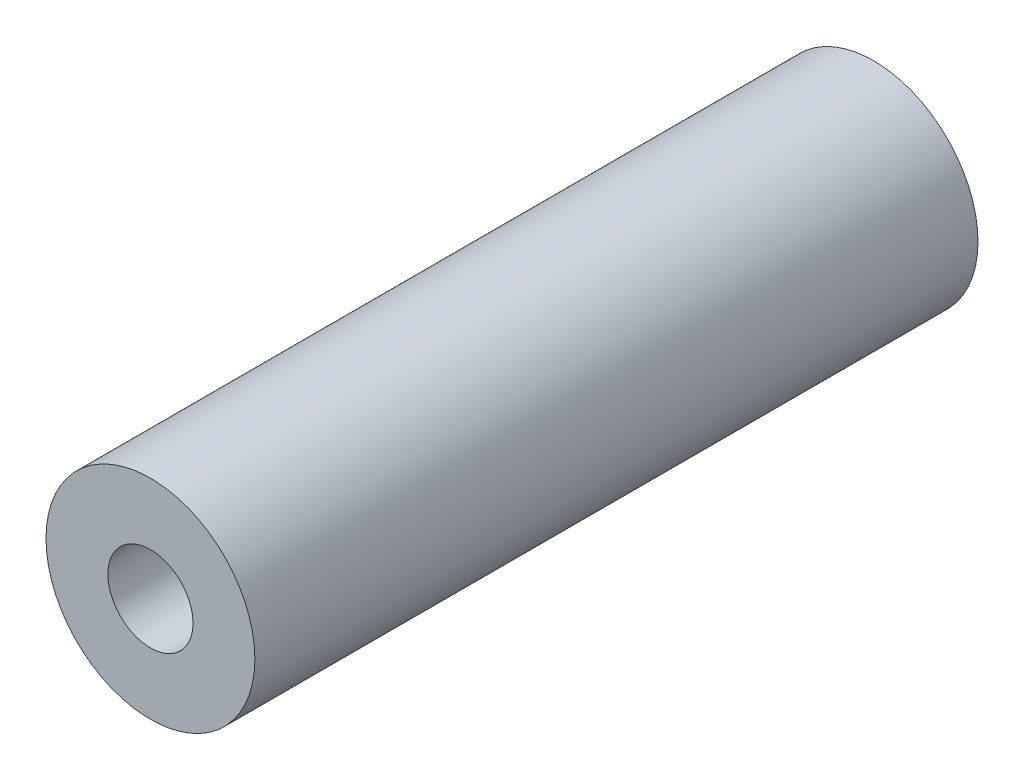
SolidWorks part; units mm, degrees
material "6061-T6 (SS)"
ref_plane "Front Plane" through (0, 0, 0) normal (0, 0, 1) x (1, 0, 0)
ref_plane "Top Plane" through (0, 0, 0) normal (0, 1, 0) x (1, 0, 0)
ref_plane "Right Plane" through (0, 0, 0) normal (1, 0, 0) x (0, 0, -1)
sketch "Sketch1" plane through (0, 0, 0) normal (0, 0, 1) x (1, 0, 0)
  circle A0 centre (0, 0) radius 6.5
  circle A1 centre (0, 0) radius 2.65
  dimension "OD" = 13
  dimension "ID" = 5.3
extrude "Extrude1" add sketch "Sketch1" along normal mid plane 45
sketch "Sketch2" plane through (0, 0, 0) normal (1, 0, 0) x (0, 0, -1)
  line L0 (-22.5, -2.65) -> (22.5, -2.65) construction
  line L3 (22.5, 2.65) -> (-22.5, 2.65) construction
  line L5 (-22.5, -2.65) -> (22.5, -2.65)
  line L6 (22.5, 2.65) -> (-22.5, 2.65)
sketch "Sketch4" plane through (0, 0, 22.5) normal (0, 0, 1) x (1, 0, 0)
  line L0 (0, 0) -> (-1.8738, 1.8738)
  line L1 (0, -7.15) -> (0, 7.15) construction
  circle A0 centre (0, 0) radius 2.65 construction
  dimension "D1" = 45
